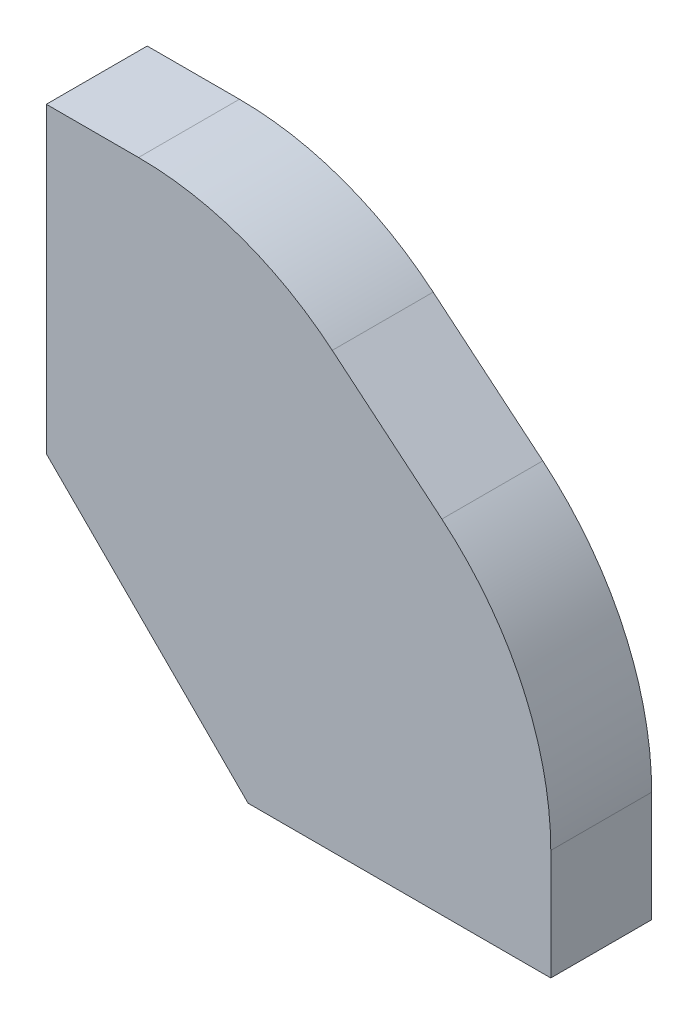
SolidWorks part; units mm, degrees
ref_plane "Plan de face" through (0, 0, 0) normal (0, 0, 1) x (1, 0, 0)
ref_plane "Plan de dessus" through (0, 0, 0) normal (0, 1, 0) x (1, 0, 0)
ref_plane "Plan de droite" through (0, 0, 0) normal (1, 0, 0) x (0, 0, -1)
sketch "Esquisse1" plane through (0, 0, 0) normal (0, 0, 1) x (1, 0, 0)
  line L0 (0, 20) -> (0, 50)
  line L1 (0, 50) -> (9.1385, 50)
  line L2 (28.344, 43.0466) -> (39.2055, 33.9954)
  line L3 (50, 10.9488) -> (50, 0)
  line L4 (50, 0) -> (20, 0)
  line L5 (20, 0) -> (0, 20)
  arc A0 (39.2055, 33.9954) -> (50, 10.9488) centre (20, 10.9488) cw
  arc A1 (9.1385, 50) -> (28.344, 43.0466) centre (9.1385, 20) cw
  point P9 (50, 25)
  point P12 (20, 50)
  dimension "D7" = 30
  dimension "D1" = 20
  dimension "D2" = 50
  dimension "D3" = 20
  dimension "D4" = 25
  dimension "D5" = 50
  dimension "D6" = 45
extrude "Boss.-Extru.1" add sketch "Esquisse1" along normal blind 10
